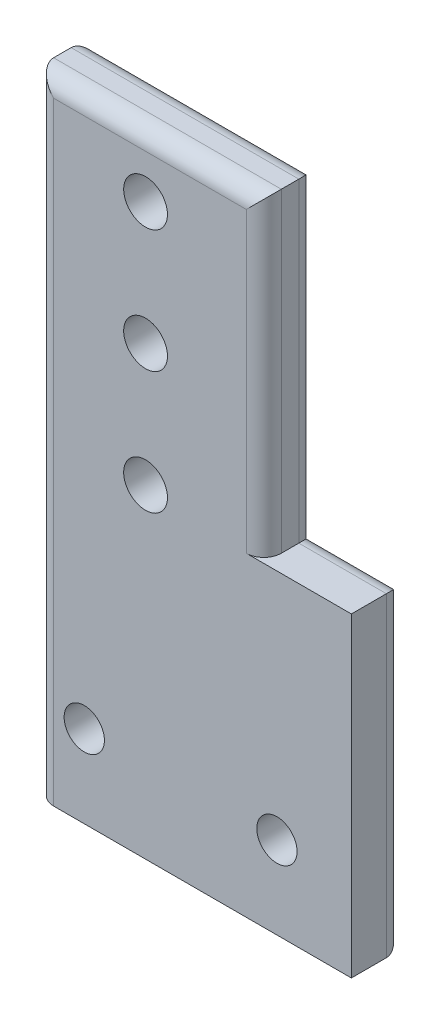
SolidWorks part; units mm, degrees
material "Custom Plastic"
ref_plane "Front Plane" through (0, 0, 0) normal (0, 0, 1) x (1, 0, 0)
ref_plane "Top Plane" through (0, 0, 0) normal (0, 1, 0) x (1, 0, 0)
ref_plane "Right Plane" through (0, 0, 0) normal (1, 0, 0) x (0, 0, -1)
sketch "Sketch1" plane through (0, 0, 0) normal (0, 0, 1) x (1, 0, 0)
  line L9 (-27.25, 21) -> (-27.25, 0) construction
  line L10 (-27.25, 21) -> (-27.25, 0)
  line L11 (-27.25, 21) -> (-14.25, 21)
  line L12 (-27.25, 21) -> (27.25, 21) construction
  line L13 (-14.25, 21) -> (-14.25, 3)
  line L15 (-27.25, -15) -> (-27.25, 0)
  line L16 (-14.25, 3) -> (-9.25, 3)
  line L17 (-9.25, 3) -> (-9.25, -15)
  line L18 (-9.25, -15) -> (-27.25, -15)
  circle A0 centre (-21, 17.5) radius 1.25 construction
  circle A1 centre (-21, 10.5) radius 1.25 construction
  circle A2 centre (-21, 3.5) radius 1.25 construction
  circle A3 centre (-21, 17.5) radius 1.25
  circle A4 centre (-21, 10.5) radius 1.25
  circle A5 centre (-21, 3.5) radius 1.25
  circle A6 centre (-13.5, -10.3) radius 1.15 construction
  circle A7 centre (-24.5, -10.3) radius 1.15 construction
  circle A8 centre (-13.5, -10.3) radius 1.15
  circle A9 centre (-24.5, -10.3) radius 1.15
  dimension "D1" = 13
  dimension "D2" = 18
  dimension "D3" = 5
  dimension "D4" = 18
extrude "Boss-Extrude1" add sketch "Sketch1" along normal blind 3
fillet "Fillet1" [suppressed] radius 1
fillet "Fillet2" radius 1 9 edges at (-18.25, -15, 0) (-9.25, -6, 0) (-11.75, 3, 0) (-14.25, 12, 0) (-20.75, 21, 0) (-27.25, 3, 0) (-20.75, 21, 3) (-14.25, 12, 3) (-27.25, 3, 3)
sketch "Sketch3" plane through (0, 0, 3) normal (0, 0, 1) x (1, 0, 0)
  line L0 (-9.25, -15) -> (-9.25, 3) construction
  line L1 (-9.25, -15) -> (-9.25, 3)
  line L2 (-9.25, -15) -> (-51.25, -15)
  line L3 (-26.25, -15) -> (-9.25, -15) construction
  line L4 (-51.25, -15) -> (-51.25, 3)
  line L5 (-9.25, 3) -> (-15.25, 3) construction
  line L6 (-51.25, 3) -> (-9.25, 3)
  dimension "D1" = 42
extrude "Boss-Extrude2" [suppressed] add sketch "Sketch3" along normal blind 13
fillet "Fillet3" [suppressed] radius 1
